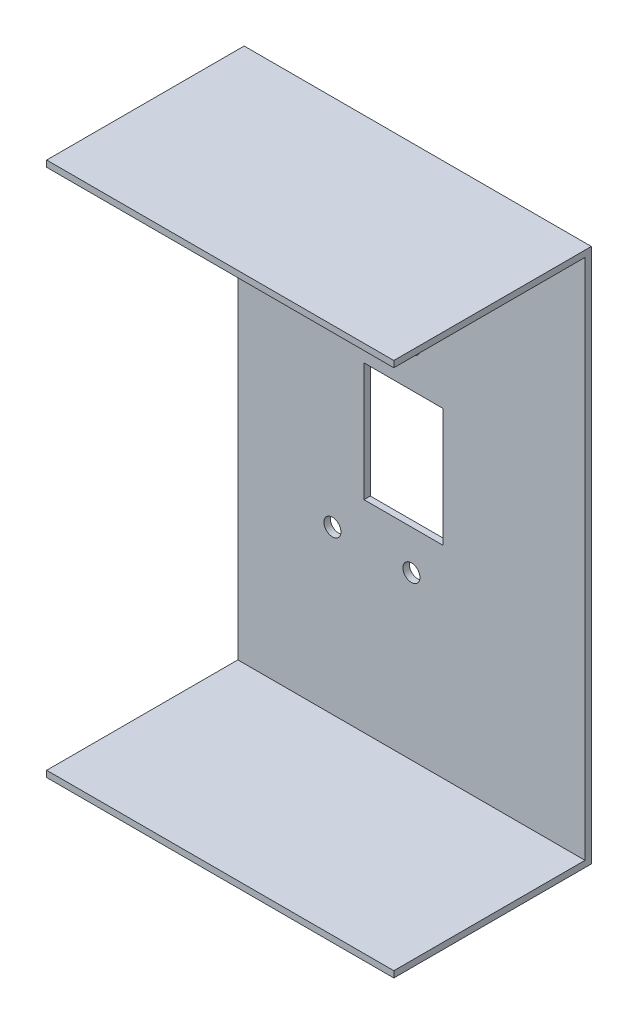
SolidWorks part; units mm, degrees
ref_plane "Front Plane" through (0, 0, 0) normal (0, 0, 1) x (1, 0, 0)
ref_plane "Top Plane" through (0, 0, 0) normal (0, 1, 0) x (1, 0, 0)
ref_plane "Right Plane" through (0, 0, 0) normal (1, 0, 0) x (0, 0, -1)
sketch "Sketch1" plane through (0, 0, 0) normal (1, 0, 0) x (0, 0, -1)
  line L0 (0, 0) -> (0, -1.6002)
  line L1 (0, -1.6002) -> (48.3998, -1.6002)
  line L2 (48.3998, -1.6002) -> (48.3998, -133.7877)
  line L3 (48.3998, -133.7877) -> (0, -133.7877)
  line L4 (0, -133.7877) -> (0, -135.3879)
  line L5 (0, -135.3879) -> (50, -135.3879)
  line L6 (50, -135.3879) -> (50, 0)
  line L7 (50, 0) -> (0, 0)
  line L8 (48.3998, -1.6002) -> (50, -1.6002) construction
  dimension "D1" = 135.3879
  dimension "D2" = 1.6002
  dimension "D3" = 50
extrude "Boss-Extrude1" add sketch "Sketch1" along normal blind 87.8907
sketch "Sketch2" plane through (0, 0, -48.3998) normal (0, 0, 1) x (1, 0, 0)
  line L0 (23.9453, -42.694) -> (23.9453, -92.694) construction
  line L1 (31.9453, -82.694) -> (51.9453, -82.694)
  line L2 (0, -67.694) -> (87.8907, -67.6939) construction
  line L3 (0, -1.6002) -> (0, -133.7877) construction
  line L4 (87.8907, -1.6002) -> (87.8907, -133.7877) construction
  line L5 (43.9453, -1.6002) -> (43.9453, -133.7877) construction
  line L6 (87.8907, -1.6002) -> (0, -1.6002) construction
  line L7 (87.8907, -133.7877) -> (0, -133.7877) construction
  line L8 (31.9453, -82.694) -> (31.9453, -52.694)
  line L9 (31.9453, -52.694) -> (51.9453, -52.694)
  line L10 (51.9453, -82.694) -> (51.9453, -52.694)
  line L11 (43.9453, -42.694) -> (43.9453, -92.694) construction
  circle A4 centre (23.9453, -92.694) radius 2.155
  circle A5 centre (23.9453, -42.694) radius 2.155
  circle A6 centre (43.9453, -92.694) radius 2.155
  circle A7 centre (43.9453, -42.694) radius 2.155
  point P1 (31.9453, -67.694)
  point P9 (23.9453, -67.694)
  dimension "D1" = 30
  dimension "D6" = 4.31
  dimension "D2" = 20
  dimension "D3" = 8
  dimension "D4" = 50
  dimension "D5" = 8
  dimension "D7" = 12
extrude "Cut-Extrude1" cut sketch "Sketch2" against normal up to surface (1.6002 mm away) up to face at (43.9453, -67.694, -50)
